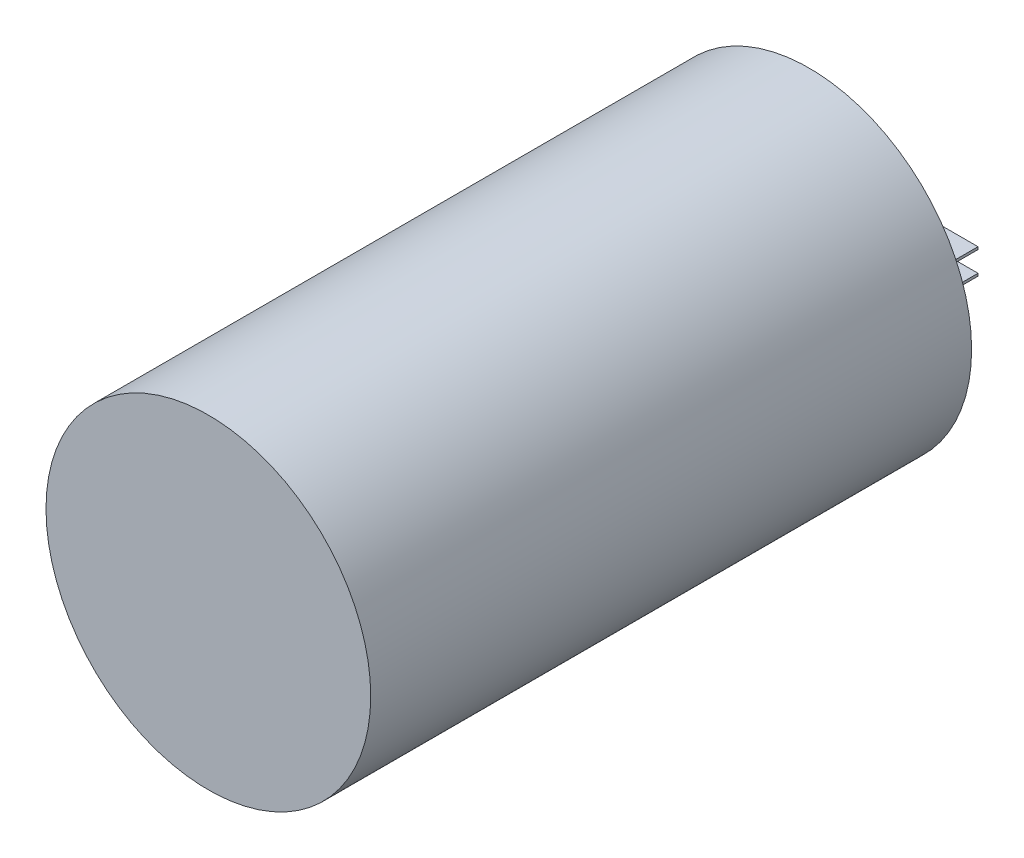
SolidWorks part; units mm, degrees
ref_plane "Front Plane" through (0, 0, 0) normal (0, 0, 1) x (1, 0, 0)
ref_plane "Top Plane" through (0, 0, 0) normal (0, 1, 0) x (1, 0, 0)
ref_plane "Right Plane" through (0, 0, 0) normal (1, 0, 0) x (0, 0, -1)
sketch "Sketch1" plane through (0, 0, 0) normal (0, 0, 1) x (1, 0, 0)
  circle A0 centre (0, 0) radius 12.7
  dimension "D1" = 25.4
extrude "Boss-Extrude1" add sketch "Sketch1" along normal blind 47
sketch "Sketch2" plane through (0, 0, 0) normal (0, 0, -1) x (-1, 0, 0)
  line L0 (-7, 1) -> (7, -1) construction
  line L1 (-7, 1) -> (7, 1)
  line L2 (-7, 1) -> (-7, -1)
  line L3 (-7, -1) -> (7, -1)
  line L4 (7, 1) -> (7, -1)
  line L5 (7, 1) -> (0, 0) construction
  dimension "D1" = 14
  dimension "D2" = 2
extrude "Boss-Extrude2" add sketch "Sketch2" along normal blind 6.2
sketch "Sketch3" plane through (0, 0, -6.2) normal (0, 0, -1) x (-1, 0, 0)
  line L0 (-7, 1) -> (-7, -1) construction
  line L1 (-7, 0.8) -> (7, 0.8)
  line L2 (-7, 0.8) -> (-7, -0.8)
  line L3 (-7, -0.8) -> (7, -0.8)
  line L4 (7, 0.8) -> (7, -0.8)
  line L5 (7, -1) -> (7, 1) construction
  line L6 (7, 1) -> (-7, 1) construction
  line L7 (-7, -1) -> (7, -1) construction
  dimension "D1" = 0.2
  dimension "D2" = 0.2
extrude "Cut-Extrude1" cut sketch "Sketch3" against normal blind 6.2
